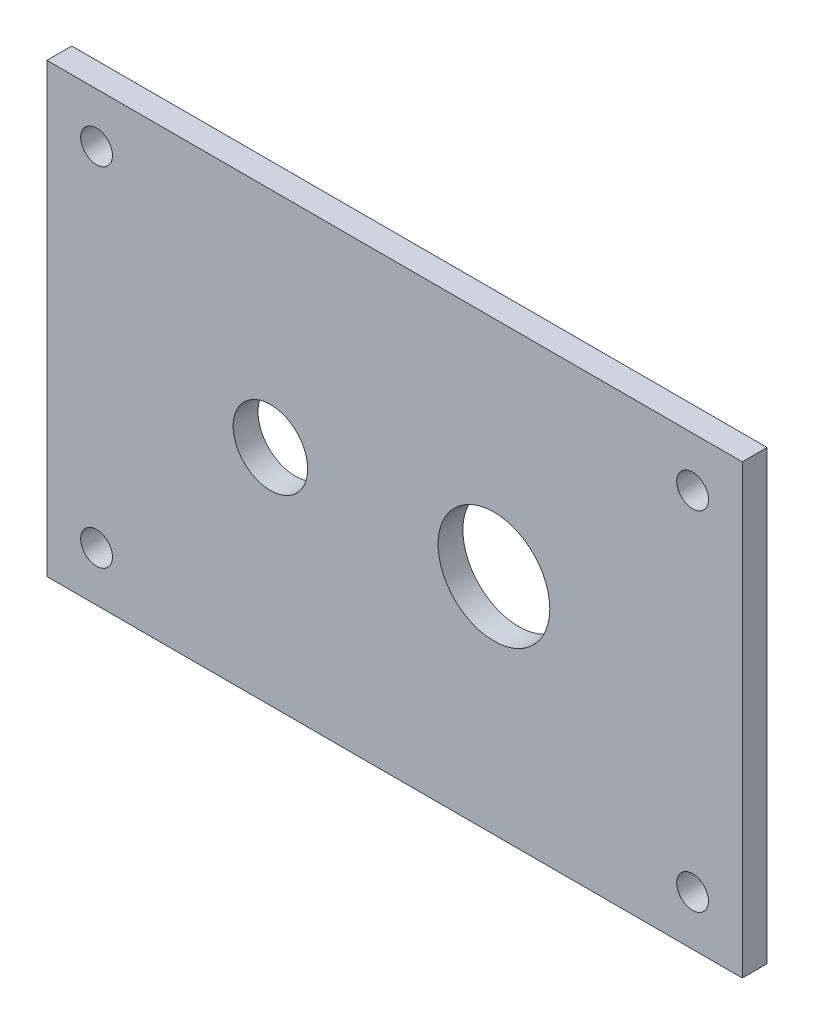
SolidWorks part; units mm, degrees
ref_plane "Front Plane" through (0, 0, 0) normal (0, 0, 1) x (1, 0, 0)
ref_plane "Top Plane" through (0, 0, 0) normal (0, 1, 0) x (1, 0, 0)
ref_plane "Right Plane" through (0, 0, 0) normal (1, 0, 0) x (0, 0, -1)
sketch "Sketch1" plane through (0, 0, 0) normal (0, 0, 1) x (1, 0, 0)
  line L0 (0, -871.3054) -> (0, 871.3054) construction
  line L1 (-1504.3228, 0) -> (1504.3228, 0) construction
  line L3 (-88.9, -57.15) -> (88.9, -57.15)
  line L4 (-88.9, -57.15) -> (-88.9, 57.15)
  line L5 (-88.9, 57.15) -> (88.9, 57.15)
  line L6 (88.9, -57.15) -> (88.9, 57.15)
  line L7 (-88.9, -57.15) -> (88.9, 57.15) construction
  line L8 (-88.9, 57.15) -> (88.9, -57.15) construction
  line L9 (-88.9, 57.15) -> (-76.2, 57.15) construction
  line L10 (-88.9, 57.15) -> (-88.9, 44.45) construction
  line L11 (-88.9, 44.45) -> (-76.2, 44.45) construction
  line L12 (-76.2, 57.15) -> (-76.2, 44.45) construction
  circle A0 centre (-31.75, 0) radius 11.43 construction
  circle A1 centre (25.4, 0) radius 46.99 construction
  circle A2 centre (25.4, 0) radius 45.72 construction
  circle A3 centre (-31.75, 0) radius 12.7 construction
  circle A4 centre (25.4, 0) radius 14.2875
  circle A5 centre (-31.75, 0) radius 9.525
  circle A6 centre (-76.2, 44.45) radius 4.064
  circle A7 centre (-76.2, -44.45) radius 4.064
  circle A8 centre (76.2, 44.45) radius 4.064
  circle A9 centre (76.2, -44.45) radius 4.064
  point P0 (0, 0)
  point P4 (0, 0)
  point P8 (0, 0)
  dimension "D1" = 91.44
  dimension "D2" = 93.98
  dimension "D3" = 22.86
  dimension "D4" = 25.4
  dimension "D8" = 28.575
  dimension "D9" = 19.05
  dimension "D12" = 8.128
  dimension "D5" = 25.4
  dimension "D6" = 114.3
  dimension "D7" = 177.8
  dimension "D10" = 12.7
  dimension "D11" = 12.7
extrude "Boss-Extrude1" add sketch "Sketch1" along normal mid plane 6.35
